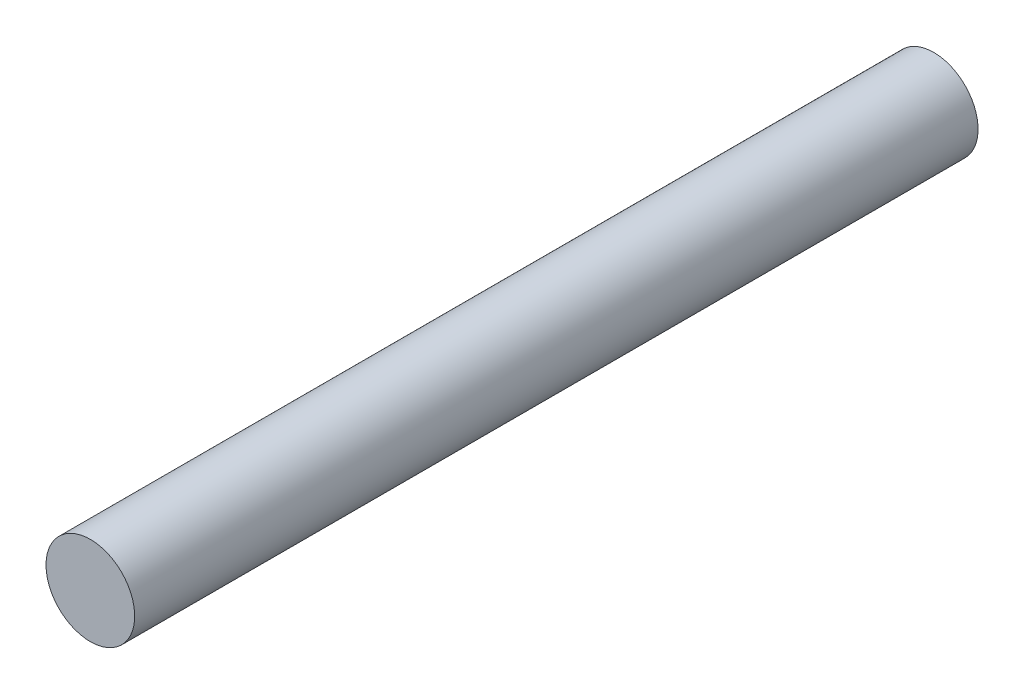
SolidWorks part; units mm, degrees
material "ASTM A36 Steel"
ref_plane "Front Plane" through (0, 0, 0) normal (0, 0, 1) x (1, 0, 0)
ref_plane "Top Plane" through (0, 0, 0) normal (0, 1, 0) x (1, 0, 0)
ref_plane "Right Plane" through (0, 0, 0) normal (1, 0, 0) x (0, 0, -1)
sketch "Sketch1" plane through (0, 0, 0) normal (0, 0, 1) x (1, 0, 0)
  circle A0 centre (0, 0) radius 5
  dimension "D1" = 10
extrude "Boss-Extrude1" add sketch "Sketch1" along normal blind 95.1
